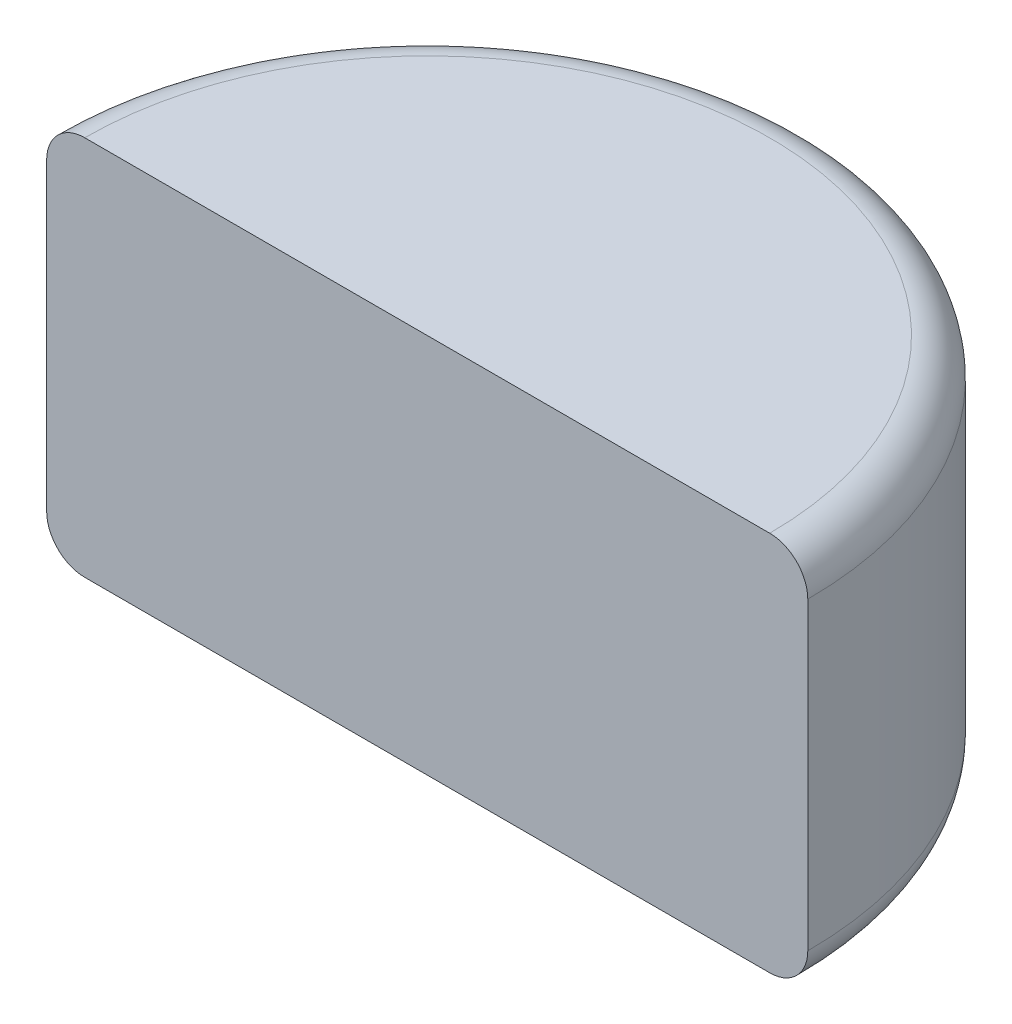
SolidWorks part; units mm, degrees
ref_plane "Front Plane" through (0, 0, 0) normal (0, 0, 1) x (1, 0, 0)
ref_plane "Top Plane" through (0, 0, 0) normal (0, 1, 0) x (1, 0, 0)
ref_plane "Right Plane" through (0, 0, 0) normal (1, 0, 0) x (0, 0, -1)
sketch "Sketch1" plane through (0, 0, 0) normal (0, 1, 0) x (1, 0, 0)
  line L0 (0, 0) -> (50.7785, 0)
  arc A0 (0, 0) -> (50.7785, 0) centre (25.3893, 0) cw
extrude "Boss-Extrude1" add sketch "Sketch1" along normal blind 25.4 contours A0 L0
fillet "Fillet1" radius 2.54 2 edges at (25.3893, 0, -25.3893) (25.3893, 25.4, -25.3893)
